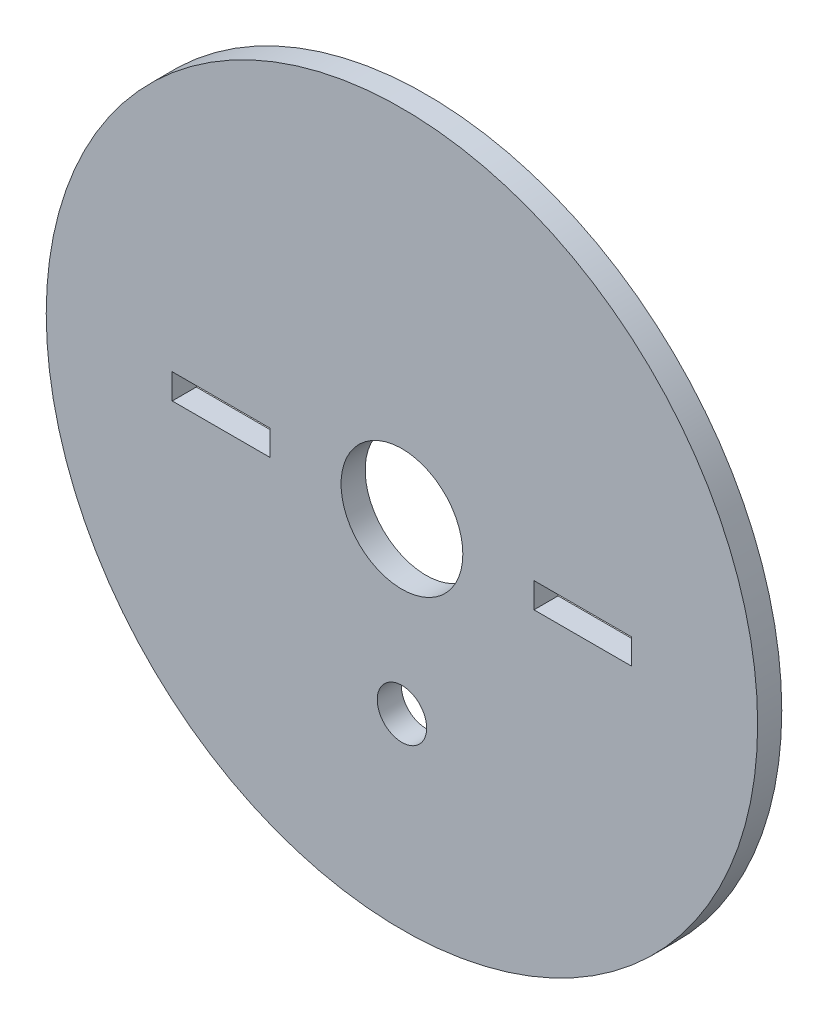
SolidWorks part; units mm, degrees
ref_plane "前视基准面" through (0, 0, 0) normal (0, 0, 1) x (1, 0, 0)
ref_plane "上视基准面" through (0, 0, 0) normal (0, 1, 0) x (1, 0, 0)
ref_plane "右视基准面" through (0, 0, 0) normal (1, 0, 0) x (0, 0, -1)
sketch "草图1" plane through (0, 0, 0) normal (0, 0, 1) x (1, 0, 0)
  line L0 (0, 0) -> (0, 14) construction
  line L1 (0, 14) -> (-15, 14) construction
  line L2 (0, 7) -> (-3.9018, 7) construction
  line L3 (-19.05, 15.05) -> (-10.95, 15.05)
  line L4 (-19.05, 15.05) -> (-19.05, 12.95)
  line L5 (-19.05, 12.95) -> (-10.95, 12.95)
  line L6 (-10.95, 15.05) -> (-10.95, 12.95)
  line L7 (-19.05, 15.05) -> (-10.95, 12.95) construction
  line L8 (-19.05, 12.95) -> (-10.95, 15.05) construction
  line L13 (10.95, 15.05) -> (10.95, 12.95)
  line L14 (19.05, 15.05) -> (10.95, 15.05)
  line L15 (19.05, 15.05) -> (19.05, 12.95)
  line L16 (19.05, 12.95) -> (10.95, 12.95)
  circle A0 centre (0, 0) radius 2.05
  circle A1 centre (0, 14) radius 2.05 construction
  circle A2 centre (0, 14) radius 5.05
  circle A4 centre (0, 14) radius 12 construction
  circle A6 centre (0, 14) radius 29.5
  circle A10 centre (0, 14) radius 3.35 construction
  dimension "D1" = 4.1
  dimension "D3" = 4.1
  dimension "D7" = 10.1
  dimension "D9" = 24
  dimension "D10" = 59
  dimension "D11" = 6.7
  dimension "D2" = 14
  dimension "D4" = 15
  dimension "D5" = 8.1
  dimension "D6" = 2.1
  dimension "D8" = 0
extrude "凸台-拉伸1" add sketch "草图1" along normal blind 2
